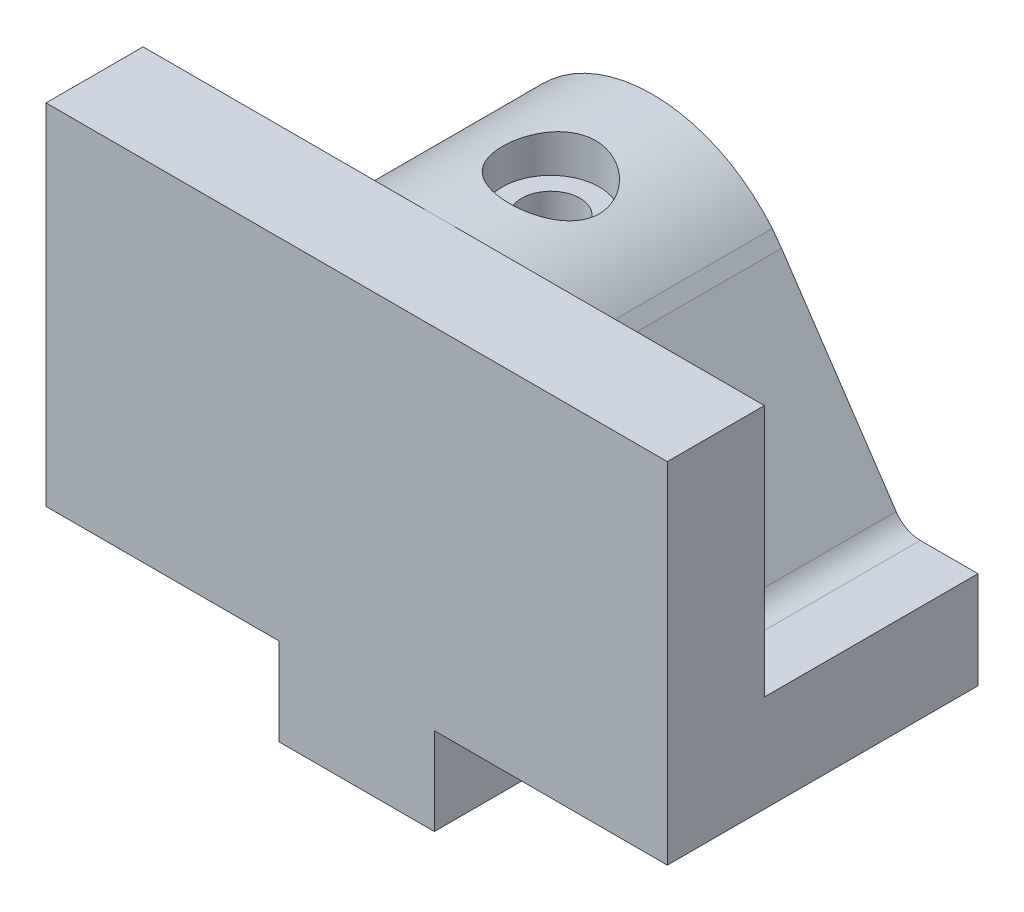
SolidWorks part; units mm, degrees
material "Gray Cast Iron"
ref_plane "Front Plane" through (0, 0, 0) normal (0, 0, 1) x (1, 0, 0)
ref_plane "Top Plane" through (0, 0, 0) normal (0, 1, 0) x (1, 0, 0)
ref_plane "Right Plane" through (0, 0, 0) normal (1, 0, 0) x (0, 0, -1)
sketch "Sketch2" plane through (0, 0, 0) normal (0, 0, 1) x (1, 0, 0)
  line L0 (-30.4794, -10) -> (-27.5791, -10)
  line L1 (30.4794, -10) -> (27.5791, -10)
  line L2 (33.5206, -10) -> (33.5206, -20)
  line L3 (33.5206, -20) -> (-30.4794, -20)
  line L4 (-30.4794, -10) -> (-30.4794, -20)
  line L5 (25.088, -8.6717) -> (13.2858, 8.9156)
  line L6 (0, 0) -> (0, -20) construction
  line L7 (-25.088, -8.6717) -> (-13.2858, 8.9156)
  line L8 (12.3335, 10.1924) -> (13.2858, 8.9156)
  line L9 (30.4794, -10) -> (31.076, -10)
  line L10 (31.076, -10) -> (33.5206, -10)
  circle A0 centre (0, 0) radius 6
  arc A1 (12.3335, 10.1924) -> (-13.2858, 8.9156) centre (0, 0) ccw
  arc A2 (25.088, -8.6717) -> (27.5791, -10) centre (27.5791, -7) ccw
  arc A3 (-25.088, -8.6717) -> (-27.5791, -10) centre (-27.5791, -7) cw
  point P0 (0, 0)
  point P14 (29.0206, -10)
  point P17 (-25.9794, -10)
  dimension "D5" = 12
  dimension "D6" = 32
  dimension "D9" = 3
  dimension "D1" = 10
  dimension "D2" = 64
  dimension "D3" = 4.5
  dimension "D4" = 4.5
  dimension "D7" = 22.78
  dimension "D8" = 20
  dimension "D10" = 1.5929
extrude "Boss-Extrude1" add sketch "Sketch2" along normal mid plane 22
sketch "Sketch3" plane through (0, 0, 11) normal (0, 0, 1) x (1, 0, 0)
  line L1 (-30.4794, -20) -> (33.5206, -20)
  line L2 (-30.4794, -20) -> (-30.4794, 16)
  line L3 (-30.4794, 16) -> (33.5206, 16)
  line L4 (33.5206, -20) -> (33.5206, 16)
  dimension "D1" = 64
  dimension "D2" = 36
extrude "Boss-Extrude2" add sketch "Sketch3" along normal blind 10
sketch "Sketch4" plane through (0, 0, -11) normal (0, 0, -1) x (-1, 0, 0)
  line L0 (-1.5206, -20) -> (6.4794, -20)
  line L1 (30.4794, -20) -> (-33.5206, -20) construction
  line L2 (-1.5206, -20) -> (-9.5206, -20)
  line L3 (-9.5206, -20) -> (-9.5206, -29)
  line L4 (6.4794, -20) -> (6.4794, -29)
  line L5 (6.4794, -29) -> (-9.5206, -29)
  dimension "D1" = 8
  dimension "D2" = 8
  dimension "D3" = 9
  dimension "D4" = 16
extrude "Boss-Extrude3" add sketch "Sketch4" against normal up to surface (32 mm away) up to face at (1.5206, -2, 21)
ref_plane "Plane1" through (0, 16, 0) normal (0, 1, 0) x (1, 0, 0)
sketch "Sketch5" plane through (0, 16, 0) normal (0, 1, 0) x (1, 0, 0)
  line L1 (4.5206, -1) -> (6.5206, -1) construction
  line L4 (1.5206, -4) -> (1.5206, -21) construction
  line L7 (-1.4794, -1) -> (1.5206, -1) construction
  circle A0 centre (1.5206, -1) radius 5
  dimension "D3" = 1.82
  dimension "D4" = 10
  dimension "D1" = 1.5206
extrude "Cut-Extrude5" cut sketch "Sketch5" against normal blind 4
sketch "Sketch7" plane through (0, 12, 0) normal (0, 1, 0) x (1, 0, 0)
  circle A2 centre (1.5206, -1) radius 3
  dimension "D1" = 6
extrude "Cut-Extrude6" cut sketch "Sketch7" against normal blind 10
sketch "Sketch8" plane through (0, -29, 0) normal (0, -1, 0) x (1, 0, 0)
  line L0 (-6.4794, -11) -> (-6.4794, 49989) construction
  line L2 (9.5206, -11) -> (9.5206, 49989) construction
  line L4 (-6.4794, -11) -> (49993.5206, -11) construction
  line L6 (1.5206, -11) -> (1.5206, 49989) construction
  line L7 (9.5206, -11) -> (-6.4794, -11) construction
  point P12 (1.5206, -11)
  point P13 (1.5206, -3)
  point P14 (1.5206, 5)
  dimension "D1" = 8
  dimension "D2" = 16
ref_plane "Plane2" through (1.5206, 0, 0) normal (1, 0, 0) x (0, 0, -1)
sketch "Sketch11" plane through (1.5206, 0, 0) normal (1, 0, 0) x (0, 0, -1)
  line L0 (3, -29) -> (3, -13)
  line L1 (-4.4819, -29) -> (-4.4819, -20.9757) construction
  line L2 (6.35, -13) -> (6.35, -29)
  line L3 (200011, -29) -> (-249989, -29) construction
  line L4 (6.35, -29) -> (3, -29)
  line L5 (3, -13) -> (3, -11.0659)
  line L6 (3, -11.0659) -> (6.35, -13)
  line L7 (3, -29) -> (-5, -29) construction
  dimension "D1" = 16
  dimension "D2" = 3.35
  dimension "D3" = 60
revolve "Cut-Revolve1" cut sketch "Sketch11" angle 360 about L5
sketch "Sketch14" plane through (1.5206, 0, 0) normal (1, 0, 0) x (0, 0, -1)
  line L0 (-5, -29) -> (-5, 49971) construction
  line L1 (3, -11.0659) -> (6.35, -13) construction
  line L2 (6.35, -13) -> (6.35, -29) construction
  line L3 (6.35, -29) -> (3, -29) construction
  line L4 (3, -29) -> (3, -11.0659) construction
  line L5 (-16.35, -29) -> (-13, -29)
  line L6 (-16.35, -13) -> (-16.35, -29)
  line L7 (-13, -11.0659) -> (-16.35, -13)
  line L8 (-13, -29) -> (-13, -11.0659)
  dimension "D1" = 8
revolve "Cut-Revolve2" cut sketch "Sketch14" angle 360 about L8
